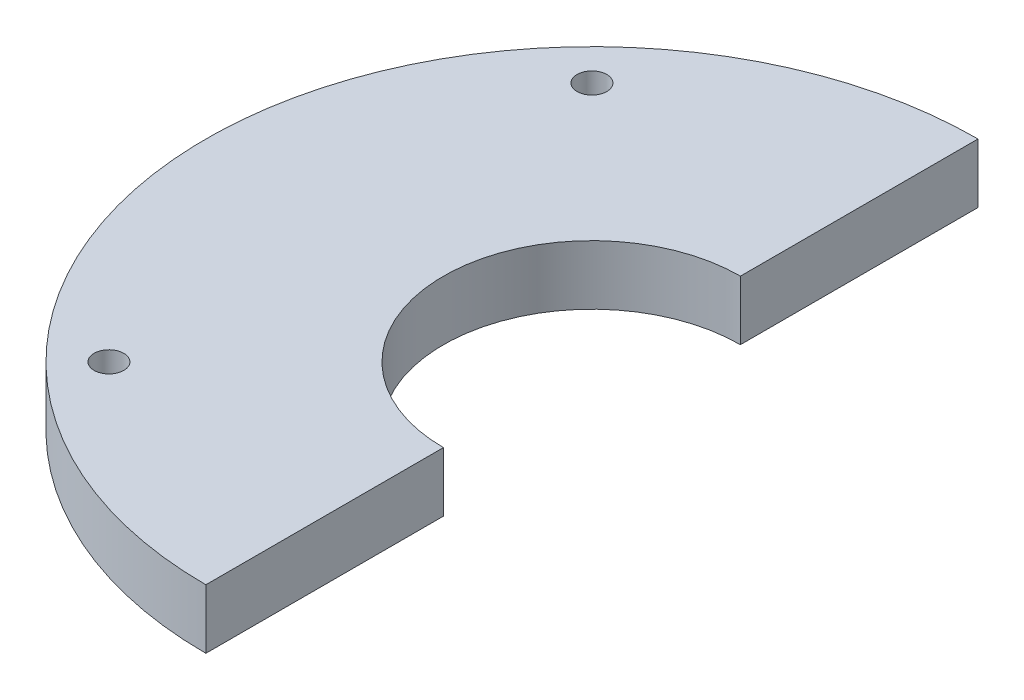
SolidWorks part; units mm, degrees
ref_plane "Front Plane" through (0, 0, 0) normal (0, 0, 1) x (1, 0, 0)
ref_plane "Top Plane" through (0, 0, 0) normal (0, 1, 0) x (1, 0, 0)
ref_plane "Right Plane" through (0, 0, 0) normal (1, 0, 0) x (0, 0, -1)
sketch "Sketch1" plane through (0, 0, 0) normal (0, 1, 0) x (1, 0, 0)
  line L0 (0, 65) -> (0, 25)
  line L1 (0, -25) -> (0, -65)
  arc A0 (0, 65) -> (0, -65) centre (0, 0) ccw
  arc A1 (0, 25) -> (0, -25) centre (0, 0) ccw
  dimension "D1" = 130
  dimension "D2" = 50
extrude "Boss-Extrude1" add sketch "Sketch1" along normal blind 10
sketch "Sketch2" plane through (0, 10, 0) normal (0, 1, 0) x (1, 0, 0)
  circle A0 centre (-40.6586, 40.6586) radius 2.5
  circle A2 centre (-40.6586, -40.6586) radius 2.5
  dimension "D3" = 5
extrude "Cut-Extrude1" cut sketch "Sketch2" against normal through all
